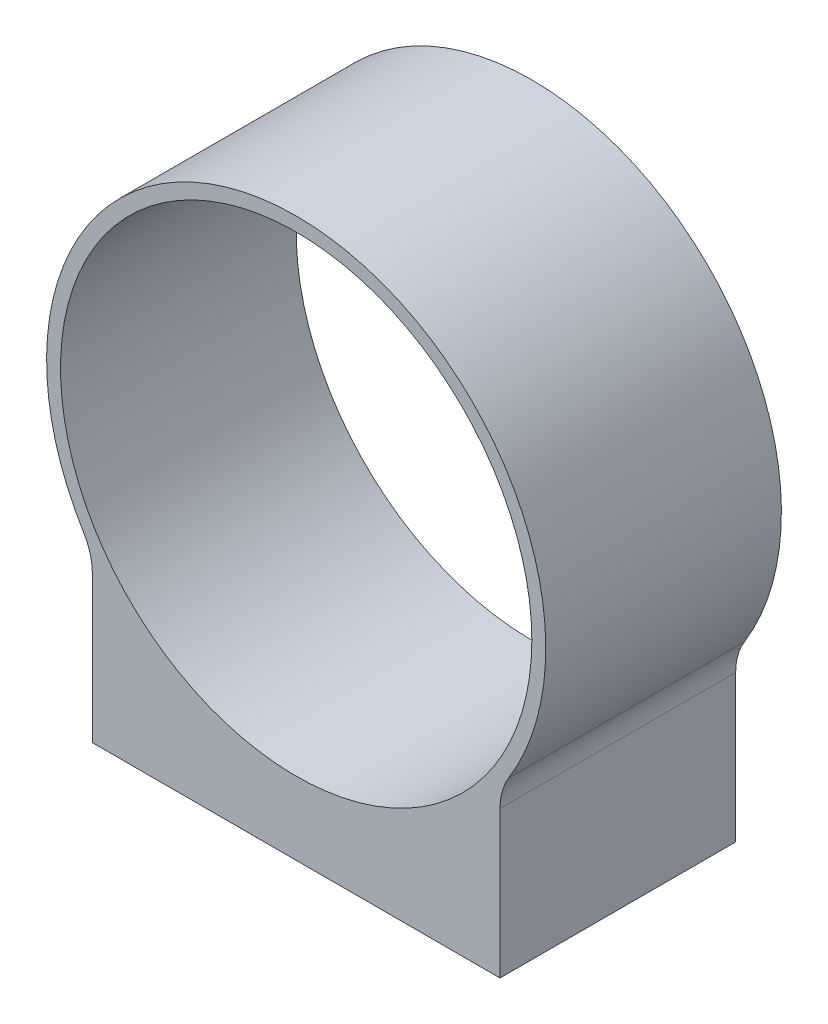
SolidWorks part; units mm, degrees
ref_plane "Front Plane" through (0, 0, 0) normal (0, 0, 1) x (1, 0, 0)
ref_plane "Top Plane" through (0, 0, 0) normal (0, 1, 0) x (1, 0, 0)
ref_plane "Right Plane" through (0, 0, 0) normal (1, 0, 0) x (0, 0, -1)
sketch "Sketch1" plane through (0, 0, 0) normal (0, 0, 1) x (1, 0, 0)
  line L0 (-0.0184, -42.3654) -> (0, -52.3654)
  line L5 (-34.5993, -24.4483) -> (34.5993, -24.4483)
  line L6 (-34.5993, -24.4483) -> (-34.5993, -52.3654)
  line L7 (-34.5993, -52.3654) -> (34.5993, -52.3654)
  line L8 (34.5993, -24.4483) -> (34.5993, -52.3654)
  circle A0 centre (0, 0) radius 40
  circle A1 centre (0, 0) radius 42.3654
  point P8 (0, 0)
  point P9 (0, -24.4483)
  point P10 (0, 0)
extrude "Boss-Extrude1" add sketch "Sketch1" along normal blind 40 contours L5 A1 A0 | L5 A1 | A1 L6 L7 L8 | A1 L6 L7 L0
ref_plane "Plane1" through (-34.5993, -52.3654, 40) normal (1, 0, 0) x (0, 0, -1)
sketch "Sketch4" plane through (0, -52.3654, 0) normal (0, -1, 0) x (-1, 0, 0)
  line L0 (34.5993, -20) -> (0, -20)
  line L1 (34.5993, -40) -> (34.5993, 0) construction
  line L2 (-34.5993, -40) -> (-34.5993, 0) construction
  line L3 (34.5993, -20) -> (0, -20)
  line L4 (0, -20) -> (-34.5993, -20)
  circle A0 centre (17.2996, -20) radius 8.6439
  circle A1 centre (-17.2996, -20) radius 8.6439
  point P7 (17.2996, -20)
  point P9 (-17.2996, -20)
  dimension "D1" = 17.2879
extrude "Cut-Extrude2" cut sketch "Sketch4" against normal blind 10 contours L3 A0 | L3 A0 | L4 A1 | L4 A1
fillet "Fillet1" radius 10 2 edges at (-34.5993, -24.4483, 20) (34.5993, -24.4483, 20)
